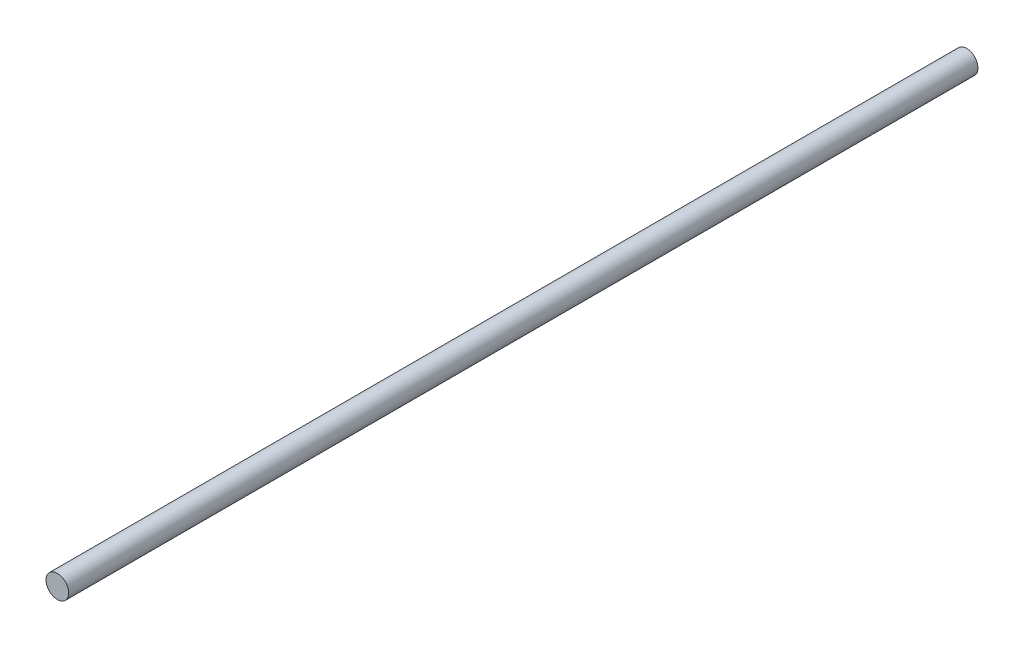
SolidWorks part; units mm, degrees
ref_plane "Plan de face" through (0, 0, 0) normal (0, 0, 1) x (1, 0, 0)
ref_plane "Plan de dessus" through (0, 0, 0) normal (0, 1, 0) x (1, 0, 0)
ref_plane "Plan de droite" through (0, 0, 0) normal (1, 0, 0) x (0, 0, -1)
sketch "Esquisse1" plane through (0, 0, 0) normal (0, 0, 1) x (1, 0, 0)
  circle A0 centre (0, 0) radius 5
  dimension "D1" = 10
extrude "Boss.-Extru.1" add sketch "Esquisse1" along normal blind 400
